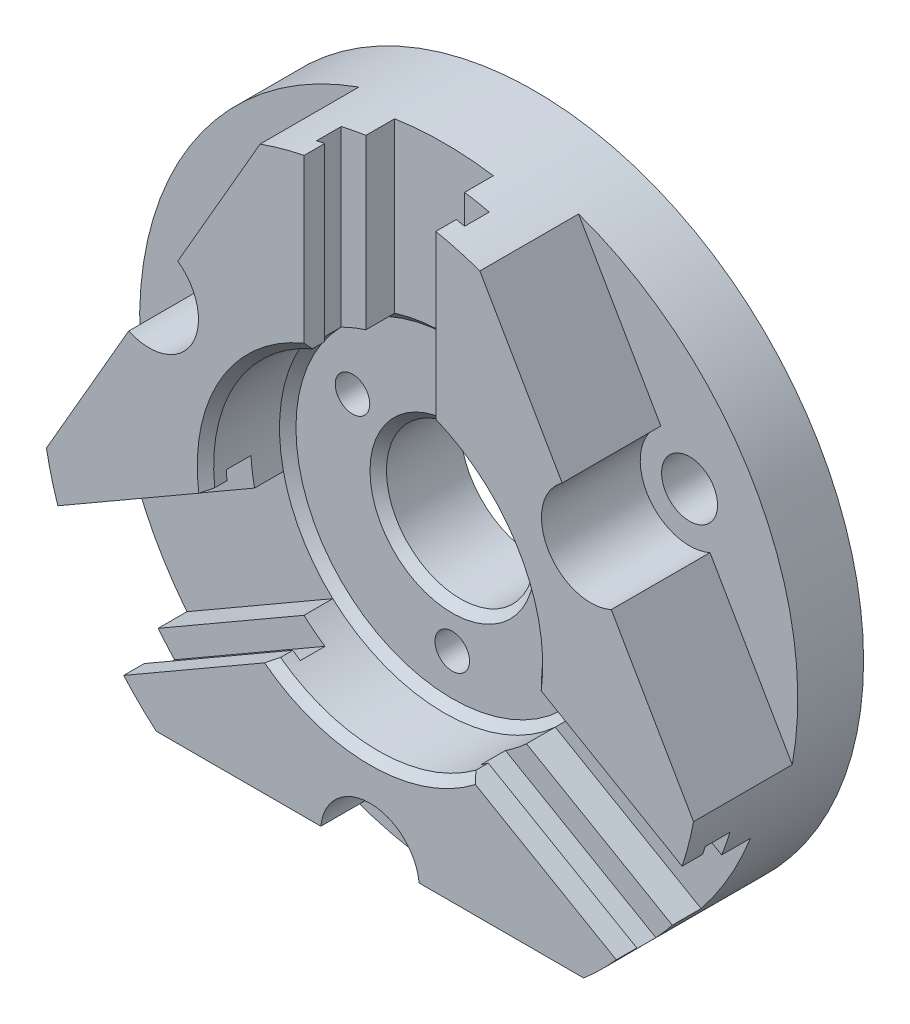
SolidWorks part; units mm, degrees
ref_plane "Front Plane" through (0, 0, 0) normal (0, 0, 1) x (1, 0, 0)
ref_plane "Top Plane" through (0, 0, 0) normal (0, 1, 0) x (1, 0, 0)
ref_plane "Right Plane" through (0, 0, 0) normal (1, 0, 0) x (0, 0, -1)
sketch "Sketch1" plane through (0, 0, 0) normal (0, 0, 1) x (1, 0, 0)
  circle A0 centre (0, 0) radius 40
  dimension "D1" = 80
extrude "Boss-Extrude1" add sketch "Sketch1" along normal blind 20
sketch "Sketch2" plane through (0, 0, 20) normal (0, 0, 1) x (1, 0, 0)
  line L0 (0, 0) -> (-59.2902, 0) construction
  line L1 (0, 0) -> (-26.8468, 15.5) construction
  line L2 (-39.3311, -7.2847) -> (-29.3299, 10.0379)
  line L3 (-23.358, 20.3814) -> (-13.3568, 37.7041)
  arc A0 (-23.358, 20.3814) -> (-31, 0) centre (0, 0) ccw construction
  arc A1 (-29.3299, 10.0379) -> (-23.358, 20.3814) centre (-26.8468, 15.5) ccw
  circle A2 centre (0, 0) radius 40 construction
  arc A3 (-13.3568, 37.7041) -> (-39.3311, -7.2847) centre (0, 0) ccw
  point P10 (0, 0)
  point P12 (0, 0)
  point P13 (0, 0)
  dimension "D1" = 62
  dimension "D3" = 6
  dimension "D2" = 30
extrude "Cut-Extrude1" cut sketch "Sketch2" against normal blind 12
pattern_circular "CirPattern1" count 3 over 360 about axis through (0, 0, 0) along (0, 0, 1) of "Cut-Extrude1"
sketch "Sketch3" plane through (0, 0, 0) normal (1, 0, 0) x (0, 0, -1)
  line L0 (0, 0) -> (-20, 0) construction
  line L1 (-20, 10.0379) -> (-20, -7.2847) construction
  line L2 (-20, 0) -> (-20, 20)
  line L3 (-20, 37.7041) -> (-20, 20.3814) construction
  line L4 (-20, 20) -> (-10, 20)
  line L5 (-10, 20) -> (-10, 9)
  line L6 (-10, 9) -> (0, 9)
  line L7 (0, -40) -> (0, 40) construction
  line L8 (0, 9) -> (0, 0)
  line L9 (0, 0) -> (-20, 0)
  dimension "D1" = 10
  dimension "D2" = 40
  dimension "D3" = 18
revolve "Cut-Revolve1" cut sketch "Sketch3" angle 360 about L0
sketch "Sketch6" plane through (0, 0, 10) normal (0, 0, 1) x (1, 0, 0)
  circle A0 centre (0, 0) radius 14 construction
  point P4 (0, -14)
  dimension "D1" = 28
hole_wizard "M5 Tapped Hole1" positions "Sketch6" profile "Sketch7" tap size "M5" standard "ISO"
cosmetic thread "Hole Thread1" parameters "D1"=10, "D2"=5
sketch "Sketch7" plane through (0, -14, 10) normal (1, 0, 0) x (0, -1, 0)
  line L0 (0, 0) -> (0, 14)
  line L1 (0, 14) -> (2.1, 12.7382)
  line L2 (2.1, 12.7382) -> (2.1, 0)
  line L5 (2.1, 0) -> (0, 0)
  line L10 (0, 14) -> (-2.1, 12.7382) construction
  line L11 (0, -6.35) -> (0, 107.95) construction
  dimension "Tap Drill Dia." = 4.2
  dimension "Tap Drill Depth" = 14
  dimension "Drill Angle" = 118
pattern_circular "CirPattern2" count 3 over 360 about axis through (0, 0, 0) along (0, 0, 1) of "M5 Tapped Hole1"
cosmetic thread "Hole Thread2" parameters "D1"=10, "D2"=5
cosmetic thread "Hole Thread3" parameters "D1"=10, "D2"=5
sketch "Sketch8" plane through (0, 0, 8) normal (0, 0, 1) x (1, 0, 0)
  line L0 (0, 0) -> (-26.8468, 15.5) construction
  circle A0 centre (0, 0) radius 31 construction
  point P7 (-26.8468, 15.5)
  point P14 (-26.8468, 15.5)
  point P18 (0, 0)
  dimension "D1" = 62
  dimension "D2" = 30
hole_wizard "M8 Tapped Hole1" positions "Sketch8" profile "Sketch9" tap size "M8" standard "ISO"
cosmetic thread "Hole Thread4" parameters "D1"=16, "D2"=8
sketch "Sketch9" plane through (-26.8468, 15.5, 8) normal (1, 0, 0) x (0, -1, 0)
  line L0 (0, 0) -> (0, 22.25)
  line L1 (0, 22.25) -> (3.4, 20.2071)
  line L2 (3.4, 20.2071) -> (3.4, 0)
  line L5 (3.4, 0) -> (0, 0)
  line L10 (0, 22.25) -> (-3.4, 20.2071) construction
  line L11 (0, -6.35) -> (0, 107.95) construction
  dimension "Tap Drill Dia." = 6.8
  dimension "Tap Drill Depth" = 22.25
  dimension "Drill Angle" = 118
pattern_circular "CirPattern3" count 3 over 360 about axis through (0, 0, 0) along (0, 0, 1) of "M8 Tapped Hole1"
cosmetic thread "Hole Thread5" parameters "D1"=16, "D2"=8
cosmetic thread "Hole Thread6" parameters "D1"=16, "D2"=8
hole_wizard "M6 Tapped Hole2" positions "Sketch10" profile "Sketch11" tap size "M6" standard "ISO" end condition through all
sketch "Sketch10" plane through (0, 0, 20) normal (0, 0, 1) x (1, 0, 0)
  line L0 (0, 0) -> (25.9808, -15) construction
  circle A0 centre (0, 0) radius 30
  point P7 (25.9808, -15)
  point P13 (25.9808, -15)
  dimension "D1" = 60
  dimension "D2" = 60
sketch "Sketch11" plane through (25.9808, -15, 20) normal (1, 0, 0) x (0, -1, 0)
  line L0 (0, 0) -> (0, 20)
  line L1 (0, 20) -> (2.5, 20)
  line L2 (2.5, 20) -> (2.5, 0)
  line L5 (2.5, 0) -> (0, 0)
  line L11 (0, -6.35) -> (0, 107.95) construction
  dimension "Thru Tap Drill Dia." = 5
  dimension "Thru Tap Drill Depth" = 20
cosmetic thread "Hole Thread7" parameters "D2"=6
chamfer "Chamfer1" distance 1 angle 45 2 edges at (-20, 0, 10) (-20, 0, 20)
sketch "Sketch12" plane through (0, 0, 0) normal (0, 1, 0) x (1, 0, 0)
  line L0 (0, 0) -> (0, -39.1375) construction
  line L1 (8, -20) -> (8, -17.5)
  line L2 (-13.3568, -20) -> (13.3568, -20) construction
  line L3 (8, -17.5) -> (9, -17.5)
  line L4 (9, -17.5) -> (9, -14.5)
  line L5 (9, -14.5) -> (6, -14.5)
  line L6 (6, -14.5) -> (6, -11)
  line L7 (6, -11) -> (-6, -11)
  line L8 (-9, -17.5) -> (-9, -14.5)
  line L9 (-6, -14.5) -> (-6, -11)
  line L10 (-8, -20) -> (-8, -17.5)
  line L11 (-9, -14.5) -> (-6, -14.5)
  line L12 (-8, -17.5) -> (-9, -17.5)
  line L13 (40, 0) -> (-40, 0) construction
  line L14 (-8, -20) -> (8, -20)
  point P15 (0, -11)
  dimension "D1" = 12
  dimension "D2" = 3
  dimension "D3" = 2.5
  dimension "D4" = 16
  dimension "D5" = 18
  dimension "D6" = 11
extrude "Cut-Extrude2" cut sketch "Sketch12" along normal up to surface (39.1918 mm away)
pattern_circular "CirPattern4" count 3 over 360 about axis through (0, 0, 0) along (0, 0, 1) of "Cut-Extrude2"
chamfer "Chamfer2" distance 1 angle 45 1 edges at (-9, 0, 10)
